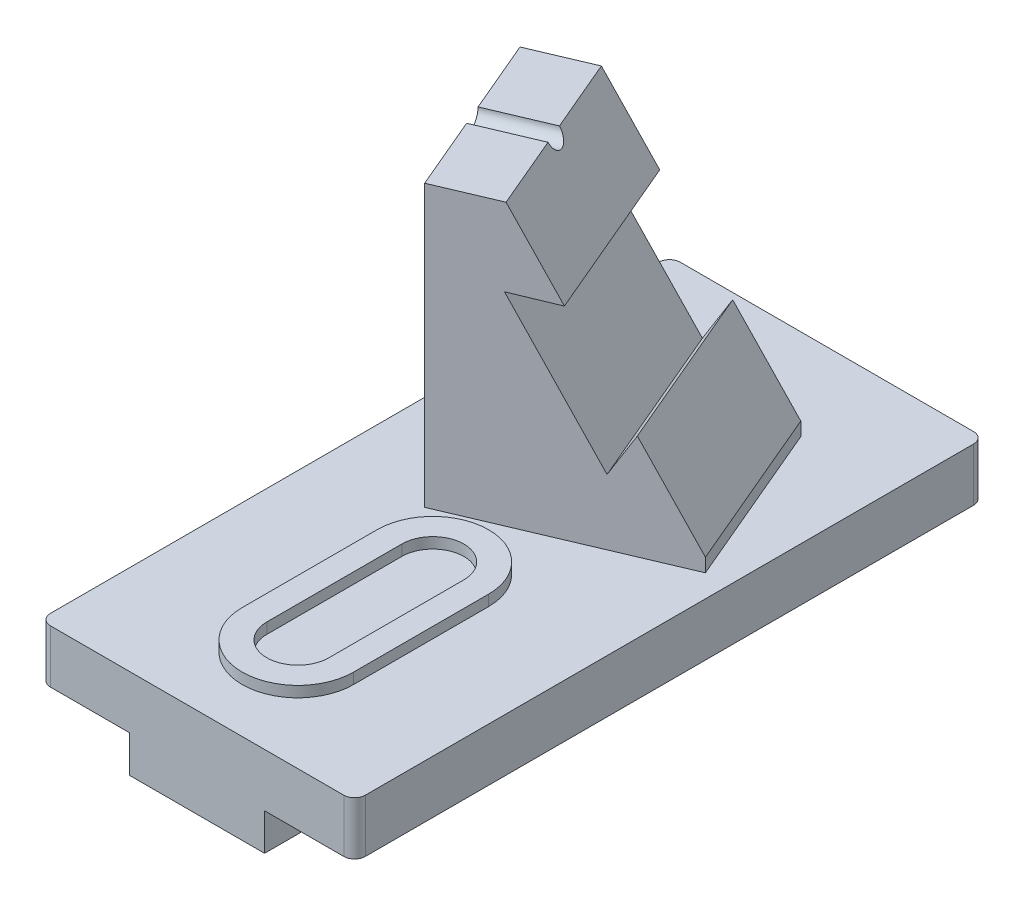
SolidWorks part; units mm, degrees
ref_plane "Front Plane" through (0, 0, 0) normal (0, 0, 1) x (1, 0, 0)
ref_plane "Top Plane" through (0, 0, 0) normal (0, 1, 0) x (1, 0, 0)
ref_plane "Right Plane" through (0, 0, 0) normal (1, 0, 0) x (0, 0, -1)
sketch "Sketch1" plane through (0, 0, 0) normal (0, 0, 1) x (1, 0, 0)
  line L0 (-175, 0) -> (175, 0)
  line L1 (175, 0) -> (175, -59)
  line L2 (175, -59) -> (75, -59)
  line L3 (75, -59) -> (75, -100)
  line L4 (75, -100) -> (-75, -100)
  line L5 (-75, -100) -> (-75, -59)
  line L6 (-75, -59) -> (-175, -59)
  line L7 (-175, -59) -> (-175, 0)
  point P3 (0, -100)
  dimension "D1" = 350
  dimension "D2" = 150
  dimension "D3" = 100
  dimension "D4" = 41
extrude "Boss-Extrude1" add sketch "Sketch1" along normal blind 700
fillet "Fillet1" radius 12 4 edges at (-175, -29.5, 0) (175, -29.5, 0) (175, -29.5, 700) (-175, -29.5, 700)
sketch "Sketch2" plane through (0, 0, 0) normal (0, 1, 0) x (1, 0, 0)
  line L0 (0, 0) -> (0, -700) construction
  line L1 (163, -700) -> (-163, -700) construction
  line L2 (0, -588) -> (0, -438) construction
  line L3 (-34.5, -588) -> (-34.5, -438)
  line L4 (34.5, -588) -> (34.5, -438)
  line L5 (-62, -588) -> (-62, -438)
  line L6 (62, -588) -> (62, -438)
  arc A0 (-34.5, -588) -> (34.5, -588) centre (0, -588) ccw
  arc A1 (34.5, -438) -> (-34.5, -438) centre (0, -438) ccw
  arc A2 (62, -438) -> (-62, -438) centre (0, -438) ccw
  arc A3 (-62, -588) -> (62, -588) centre (0, -588) ccw
  point P7 (0, -513)
  dimension "D3" = 262
  dimension "D1" = 69
  dimension "D2" = 150
  dimension "D4" = 27.5
extrude "Boss-Extrude2" add sketch "Sketch2" along normal blind 12
sketch "Sketch3" plane through (0, 0, 0) normal (0, 1, 0) x (1, 0, 0)
  line L0 (150, -285) -> (-69.0802, -377.994)
  line L1 (163, -700) -> (-163, -700) construction
  line L2 (175, -688) -> (175, -12) construction
  point P2 (0, 0)
  dimension "D1" = 415
  dimension "D2" = 23
  dimension "D3" = 25
  dimension "D4" = 238
ref_plane "Plane1" through (125.4065, 0, 295.4393) normal (-0.3907, 0, -0.9205) x (-0.9205, 0, 0.3907)
sketch "Sketch4" plane through (125.4065, 0, 295.4393) normal (-0.3907, 0, -0.9205) x (-0.9205, 0, 0.3907)
  line L0 (-26.7174, 0) -> (211.2826, 0) construction
  line L1 (-26.7174, 0) -> (211.2826, 0)
  line L2 (211.2826, 0) -> (211.2826, 312)
  line L3 (211.2826, 312) -> (142.2826, 312)
  line L4 (142.2826, 312) -> (92.8264, 225.0858)
  line L10 (31.0061, 116.443) -> (56.6848, 72.6031)
  line L11 (56.6848, 72.6031) -> (143.6322, 225.4042)
  line L12 (143.6322, 225.4042) -> (92.8264, 225.0858)
  line L13 (-26.7174, 0) -> (-26.7174, 15)
  line L14 (-26.7174, 15) -> (31.0061, 116.443)
  dimension "D1" = 312
  dimension "D2" = 100
  dimension "D3" = 69
  dimension "D4" = 125
  dimension "D5" = 60
  dimension "D6" = 60
  dimension "D7" = 44
  dimension "D8" = 15
extrude "Boss-Extrude3" add sketch "Sketch4" along normal blind 200
sketch "Sketch5" plane through (-194.4867, 0, 82.5547) normal (-0.9205, 0, 0.3907) x (0.3907, 0, 0.9205)
  line L0 (120.9536, 312) -> (320.9536, 312) construction
  arc A0 (208.9536, 312) -> (232.9536, 312) centre (220.9536, 312) ccw
  point P3 (0, 0)
  dimension "D1" = 12
extrude "Cut-Extrude1" cut sketch "Sketch5" against normal through all and the other way through all
